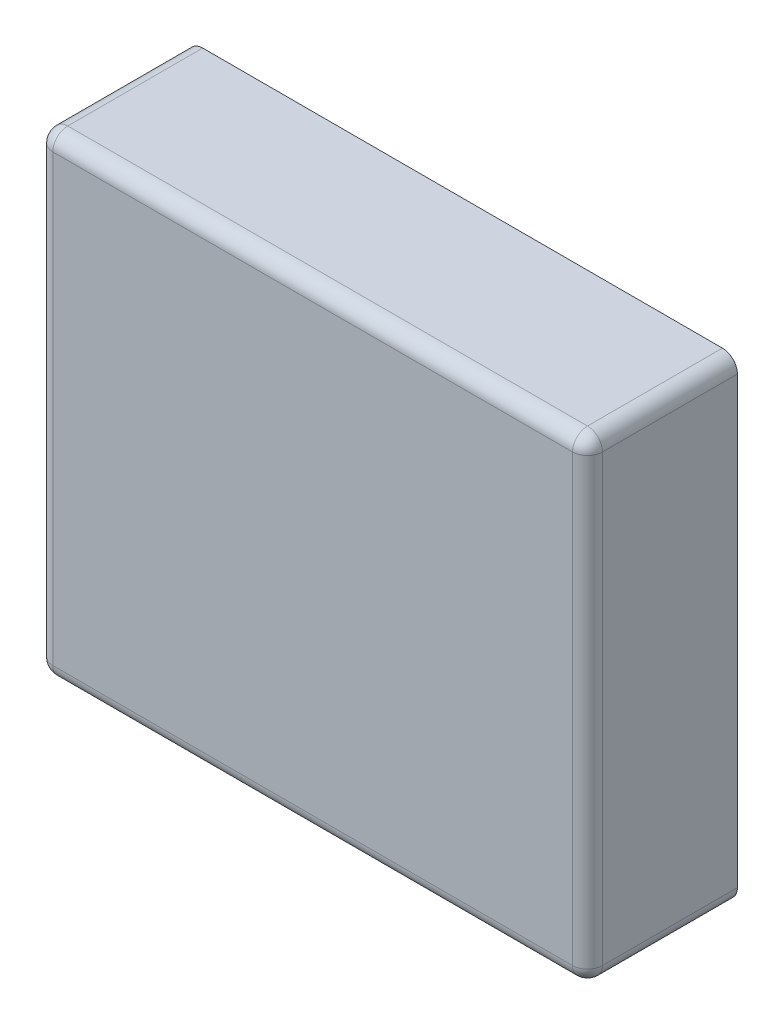
SolidWorks part; units mm, degrees
ref_plane "Front Plane" through (0, 0, 0) normal (0, 0, 1) x (1, 0, 0)
ref_plane "Top Plane" through (0, 0, 0) normal (0, 1, 0) x (1, 0, 0)
ref_plane "Right Plane" through (0, 0, 0) normal (1, 0, 0) x (0, 0, -1)
sketch "Sketch2" plane through (0, 0, 0) normal (0, 0, 1) x (1, 0, 0)
  line L1 (-54.9941, 30.5065) -> (55.0059, 30.5065)
  line L2 (-54.9941, 30.5065) -> (-54.9941, -64.4935)
  line L3 (-54.9941, -64.4935) -> (55.0059, -64.4935)
  line L4 (55.0059, 30.5065) -> (55.0059, -64.4935)
  dimension "D1" = 110
  dimension "D2" = 95
extrude "Boss-Extrude2" add sketch "Sketch2" along normal blind 30
fillet "Fillet3" radius 3 8 edges at (-54.9941, -16.9935, 30) (0.0059, 30.5065, 30) (55.0059, -16.9935, 30) (0.0059, -64.4935, 30) (-54.9941, -64.4935, 15) (55.0059, -64.4935, 15) (-54.9941, 30.5065, 15) (55.0059, 30.5065, 15)
shell "Shell1" thickness 1
